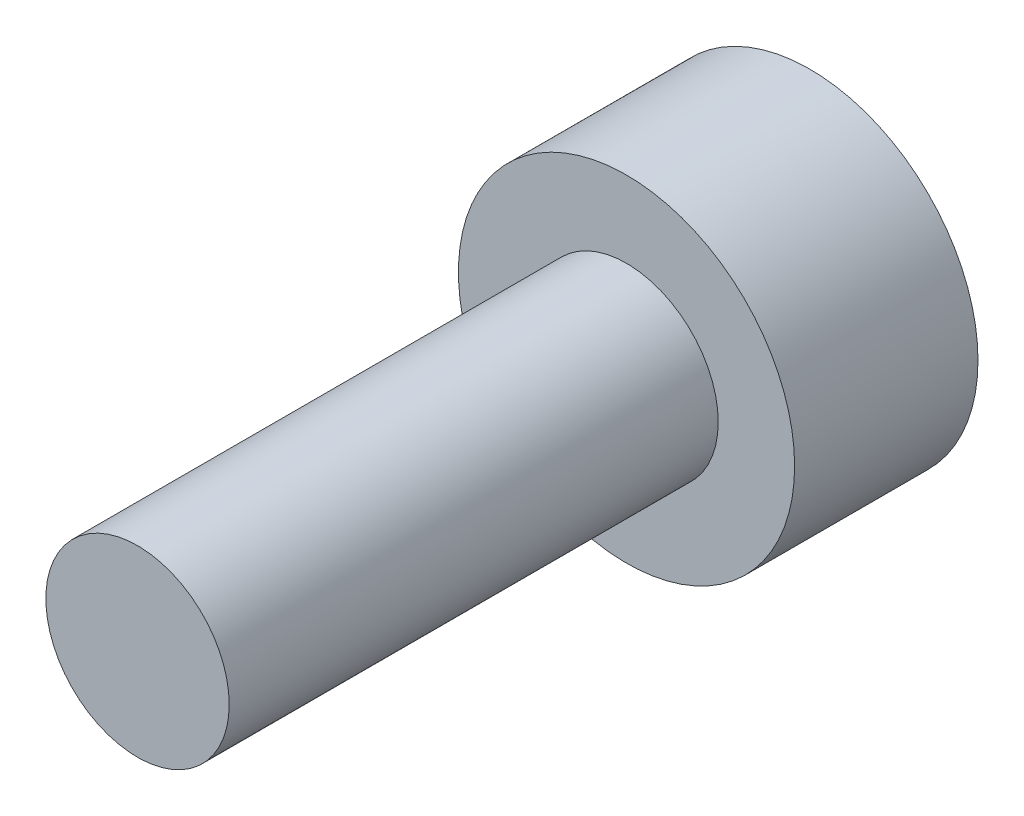
SolidWorks part; units mm, degrees
ref_plane "Front Plane" through (0, 0, 0) normal (0, 0, 1) x (1, 0, 0)
ref_plane "Top Plane" through (0, 0, 0) normal (0, 1, 0) x (1, 0, 0)
ref_plane "Right Plane" through (0, 0, 0) normal (1, 0, 0) x (0, 0, -1)
sketch "S01 - Head" plane through (0, 0, 0) normal (0, 0, 1) x (1, 0, 0)
  circle A0 centre (0, 0) radius 2.75
  dimension "D1" = 5.5
extrude "01 - Head" add sketch "S01 - Head" along normal blind 3 from offset 3
sketch "S02 - Nominal shank" plane through (0, 0, 0) normal (0, 0, 1) x (1, 0, 0)
  circle A0 centre (0, 0) radius 1.5
  dimension "D1" = 3
extrude "02 - Nominal shank" add sketch "S02 - Nominal shank" along normal blind 8
sketch "S03 - Hex key socket" plane through (0, 0, 0) normal (0, 0, 1) x (1, 0, 0)
  line L0 (1.4434, 0) -> (0.7217, 1.25)
  line L1 (0.7217, 1.25) -> (-0.7217, 1.25)
  line L2 (-0.7217, 1.25) -> (-1.4434, 0)
  line L3 (-1.4434, 0) -> (-0.7217, -1.25)
  line L4 (-0.7217, -1.25) -> (0.7217, -1.25)
  line L5 (0.7217, -1.25) -> (1.4434, 0)
  dimension "D1" = 0.7217
  dimension "D2" = 1.4434
  dimension "D3" = 0.7217
  dimension "D4" = 1.4434
  dimension "D5" = 1.25
  dimension "D6" = 1.25
extrude "03 - Hex key socket" cut sketch "S03 - Hex key socket" along normal blind 1.75 from offset 3.1
